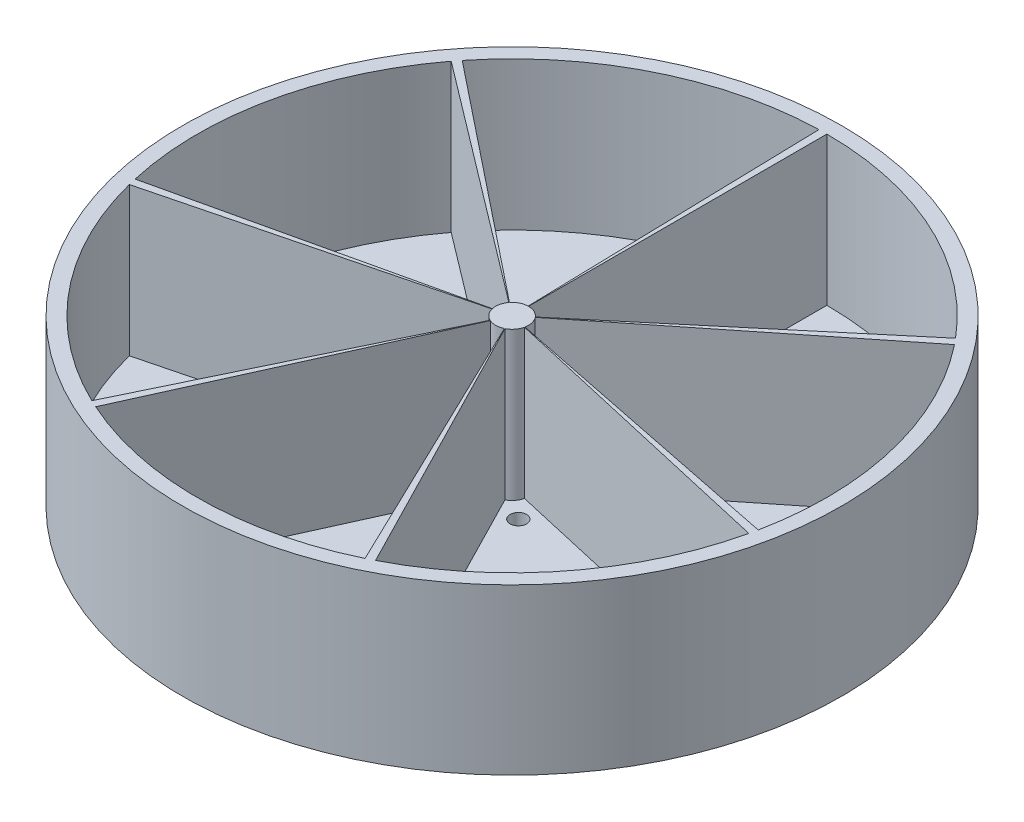
SolidWorks part; units mm, degrees
ref_plane "Front Plane" through (0, 0, 0) normal (0, 0, 1) x (1, 0, 0)
ref_plane "Top Plane" through (0, 0, 0) normal (0, 1, 0) x (1, 0, 0)
ref_plane "Right Plane" through (0, 0, 0) normal (1, 0, 0) x (0, 0, -1)
sketch "Sketch1" plane through (0, 0, 0) normal (0, 0, 1) x (1, 0, 0)
  line L1 (0, 0) -> (100, 0)
  line L2 (0, 0) -> (0, 50)
  line L3 (0, 50) -> (100, 50)
  line L4 (100, 0) -> (100, 50)
  dimension "D1" = 100
  dimension "D2" = 50
revolve "Revolve1" add sketch "Sketch1" angle 360 about L2
sketch "Sketch2" plane through (0, 50, 0) normal (0, 1, 0) x (1, 0, 0)
  line L0 (0, 5) -> (0, 95.5167)
  line L1 (3.8302, 3.2139) -> (73.17, 61.397)
  line L2 (3.9092, 3.1174) -> (74.678, 59.5537)
  line L3 (4.9009, -0.9907) -> (93.6229, -18.9263)
  line L4 (4.8746, -1.1126) -> (93.1219, -21.2545)
  line L5 (2.2811, -4.4494) -> (43.5757, -84.9976)
  line L6 (2.1694, -4.5048) -> (41.4431, -86.0576)
  line L7 (-2.0564, -4.5575) -> (-39.2848, -87.064)
  line L8 (-2.1694, -4.5048) -> (-41.4431, -86.0576)
  line L9 (-4.8454, -1.2338) -> (-92.5631, -23.5695)
  line L10 (-4.8746, -1.1126) -> (-93.1219, -21.2545)
  line L11 (-3.9857, 3.019) -> (-76.1395, 57.6734)
  line L12 (-3.9092, 3.1174) -> (-74.678, 59.5537)
  line L13 (-0.1247, 4.9984) -> (-2.3813, 95.487)
  arc A0 (73.17, 61.397) -> (0, 95.5167) centre (0, 0) ccw
  arc A1 (3.8302, 3.2139) -> (0, 5) centre (0, 0) ccw
  arc A2 (4.9009, -0.9907) -> (3.9092, 3.1174) centre (0, 0) ccw
  arc A3 (93.6229, -18.9263) -> (74.678, 59.5537) centre (0, 0) ccw
  arc A4 (2.2811, -4.4494) -> (4.8746, -1.1126) centre (0, 0) ccw
  arc A5 (43.5757, -84.9976) -> (93.1219, -21.2545) centre (0, 0) ccw
  arc A6 (-2.0564, -4.5575) -> (2.1694, -4.5048) centre (0, 0) ccw
  arc A7 (-39.2848, -87.064) -> (41.4431, -86.0576) centre (0, 0) ccw
  arc A8 (-4.8454, -1.2338) -> (-2.1694, -4.5048) centre (0, 0) ccw
  arc A9 (-92.5631, -23.5695) -> (-41.4431, -86.0576) centre (0, 0) ccw
  arc A10 (-3.9857, 3.019) -> (-4.8746, -1.1126) centre (0, 0) ccw
  arc A11 (-76.1395, 57.6734) -> (-93.1219, -21.2545) centre (0, 0) ccw
  arc A12 (-0.1247, 4.9984) -> (-3.9092, 3.1174) centre (0, 0) ccw
  arc A13 (-2.3813, 95.487) -> (-74.678, 59.5537) centre (0, 0) ccw
  point P32 (0, 0)
  dimension "D2" = 10
  dimension "D1" = 50
  dimension "D3" = 7
extrude "Cut-Extrude4" cut sketch "Sketch2" against normal blind 45
sketch "Sketch3" plane through (0, 0, 0) normal (0, -1, 0) x (1, 0, 0)
  circle A0 centre (0, 11) radius 2.5
  circle A1 centre (9.382, 7.4819) radius 2.5
  circle A2 centre (12.481, -2.0468) radius 2.5
  circle A3 centre (6.9634, -10.4107) radius 2.5
  circle A4 centre (-3.016, -11.3116) radius 2.5
  circle A5 centre (-9.9424, -4.0712) radius 2.5
  circle A6 centre (-8.6001, 5.8584) radius 2.5
  point P18 (1.0383, -0.5)
  dimension "D2" = 5
  dimension "D1" = 11
  dimension "D3" = 7
extrude "Cut-Extrude5" cut sketch "Sketch3" against normal blind 10
